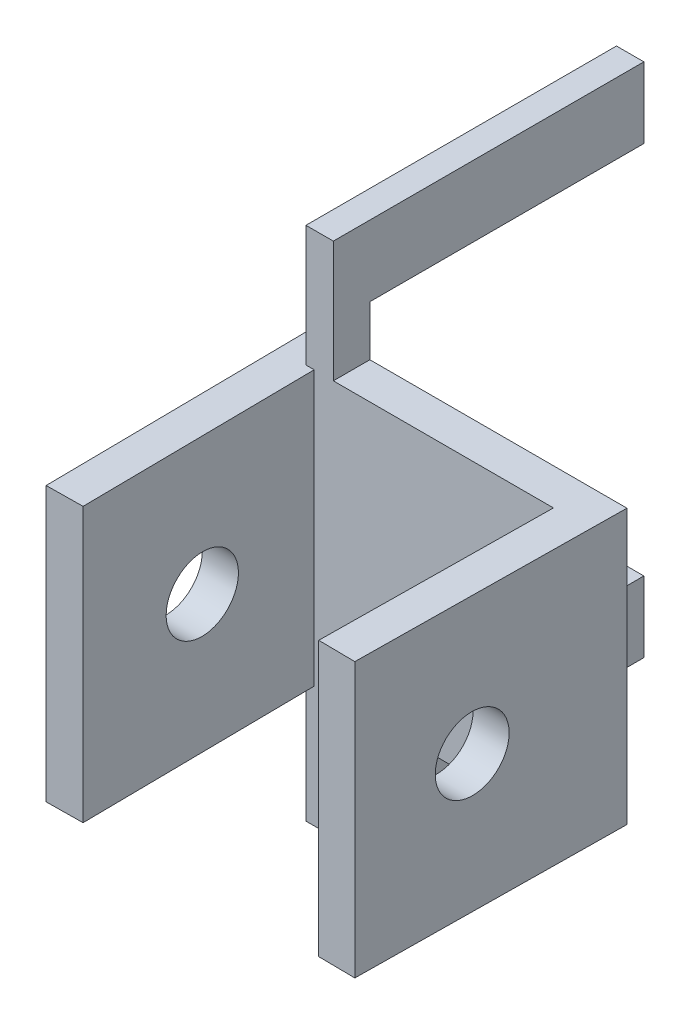
SolidWorks part; units mm, degrees
ref_plane "Front Plane" through (0, 0, 0) normal (0, 0, 1) x (1, 0, 0)
ref_plane "Top Plane" through (0, 0, 0) normal (0, 1, 0) x (1, 0, 0)
ref_plane "Right Plane" through (0, 0, 0) normal (1, 0, 0) x (0, 0, -1)
sketch "Sketch1" plane through (0, 0, 0) normal (0, 1, 0) x (1, 0, 0)
  line L0 (-12.8, -12.8) -> (-13.1, 12.8)
  line L1 (-12.8, 12.8) -> (12.8, 12.8) construction
  line L2 (-12.8, 12.8) -> (-12.8, -12.8) construction
  line L4 (12.8, 12.8) -> (12.8, -12.6) construction
  line L5 (-13.1, 12.8) -> (13.1, 12.8)
  line L6 (13.1, 12.8) -> (12.8, -12.6)
  line L7 (-16.7997, -12.8469) -> (-17.1471, 16.8)
  line L8 (-17.1471, 16.8) -> (17.1475, 16.8)
  line L9 (17.1475, 16.8) -> (16.7997, -12.6472)
  line L11 (-16.7997, -12.8469) -> (-12.8, -12.8)
  line L12 (12.8, -12.6) -> (16.7997, -12.6472)
  dimension "D1" = 25.6
  dimension "D2" = 25.4
  dimension "D3" = 0.3
  dimension "D4" = 0.3
  dimension "D5" = 4
extrude "Boss-Extrude1" add sketch "Sketch1" along normal blind 30
sketch "Sketch2" plane through (0, 30, 0) normal (0, 1, 0) x (1, 0, 0)
  line L0 (0.0002, 16.8) -> (0.0002, 30.8112) construction
  line L1 (17.1475, 16.8) -> (-17.1471, 16.8) construction
  line L2 (0.0002, 36.8) -> (-4.0998, 36.8) construction
  line L3 (0.0002, 36.8) -> (2.1002, 36.8) construction
  line L4 (-4.0998, 36.8) -> (-4.0998, 23.7851)
  line L5 (-2.0998, 36.8) -> (-2.0998, 23.7851)
  line L6 (-11.0849, 16.8) -> (-5.4334, 16.8)
  line L7 (-4.0998, 36.8) -> (-2.0998, 36.8)
  line L8 (4.1002, 36.8) -> (2.1002, 36.8)
  line L9 (11.0853, 16.8) -> (5.4337, 16.8)
  line L10 (2.1002, 36.8) -> (2.1002, 23.7851)
  line L11 (4.1002, 36.8) -> (4.1002, 23.7851)
  arc A0 (-4.0998, 23.7851) -> (-11.0849, 16.8) centre (-11.0849, 23.7851) cw
  arc A1 (-2.0998, 23.7851) -> (-5.4334, 16.8) centre (-11.0849, 23.7851) cw
  arc A2 (-2.0998, 23.7851) -> (-11.0849, 14.8) centre (-11.0849, 23.7851) cw construction
  arc A3 (4.1002, 23.7851) -> (11.0853, 16.8) centre (11.0853, 23.7851) ccw
  arc A4 (2.1002, 23.7851) -> (5.4337, 16.8) centre (11.0853, 23.7851) ccw
  dimension "D1" = 20
  dimension "D2" = 4.1
  dimension "D3" = 2
sketch "Sketch3" plane through (16.9467, 0, 0.2002) normal (0.9999, 0, 0.0118) x (0.0118, 0, -0.9999)
  line L0 (-12.448, 0) -> (12.952, 0) construction
  line L1 (0.252, 0) -> (0.252, 30) construction
  line L5 (-12.448, 30) -> (17.0013, 30) construction
  circle A0 centre (0.252, 15) radius 4
extrude "Cut-Extrude1" cut sketch "Sketch3" against normal blind 40
sketch "Sketch4" plane through (0, 0, -16.8) normal (0, 0, -1) x (-1, 0, 0)
  line L0 (17.1471, 0) -> (-17.1475, 30) construction
  line L1 (-0.0002, 15) -> (10.9998, 15) construction
  line L2 (10.9998, -5.5) -> (10.9998, 35.5)
  line L3 (10.9998, 35.5) -> (13.9998, 35.5)
  line L4 (10.9998, -5.5) -> (13.9998, -5.5)
  line L6 (13.9998, 35.5) -> (13.9998, -5.5)
  point P8 (10.9998, 15)
  dimension "D1" = 3
extrude "Boss-Extrude2" add sketch "Sketch4" against normal blind 4
sketch "Sketch5" plane through (0, 0, -16.8) normal (0, 0, -1) x (-1, 0, 0)
  line L1 (13.9998, 35.5) -> (13.9998, 43.25)
  line L11 (10.9998, 35.5) -> (10.9998, 43.25)
  line L17 (10.9998, 35.5) -> (13.9998, 35.5)
  line L18 (10.9998, 43.25) -> (13.9998, 43.25)
  line L21 (17.1471, 15) -> (-23.8791, 15) construction
  line L22 (17.1471, 30) -> (17.1471, 0) construction
  line L23 (10.9998, -13.25) -> (13.9998, -13.25)
  line L24 (10.9998, -5.5) -> (13.9998, -5.5)
  line L25 (10.9998, -5.5) -> (10.9998, -13.25)
  line L26 (13.9998, -5.5) -> (13.9998, -13.25)
extrude "Boss-Extrude3" add sketch "Sketch5" against normal blind 4 and the other way blind 30
